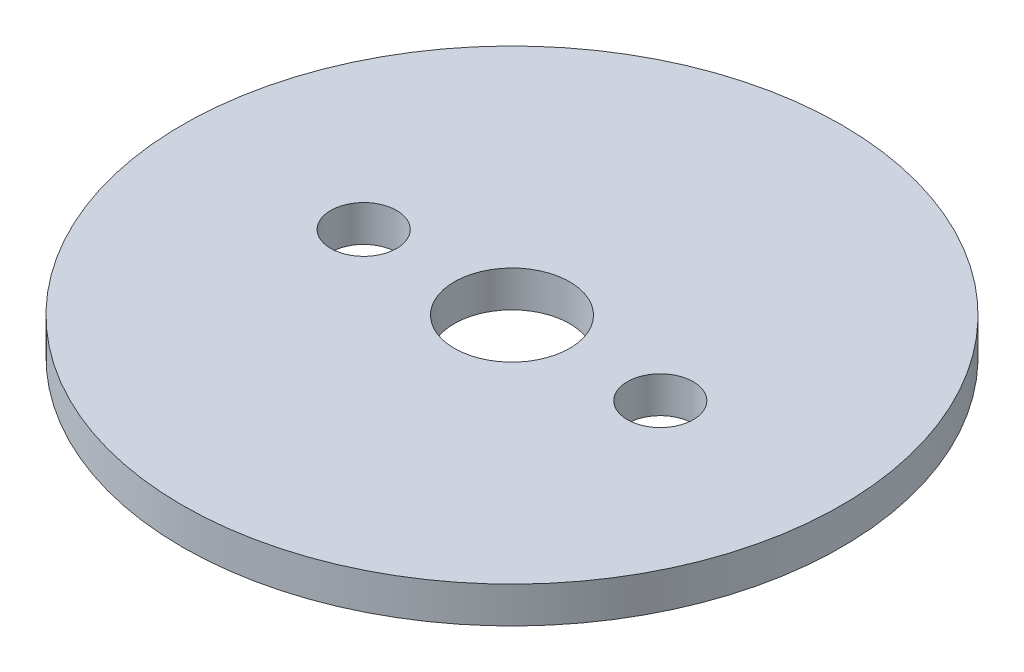
SolidWorks part; units mm, degrees
ref_plane "Спереди" through (0, 0, 0) normal (0, 0, 1) x (1, 0, 0)
ref_plane "Сверху" through (0, 0, 0) normal (0, 1, 0) x (1, 0, 0)
ref_plane "Справа" through (0, 0, 0) normal (1, 0, 0) x (0, 0, -1)
other "Configuration Table"
sketch "Эскиз1" plane through (0, 0, 0) normal (0, 1, 0) x (1, 0, 0)
  circle A0 centre (0, 0) radius 100
  circle A1 centre (0, 0) radius 17.5
  circle A2 centre (-45, 0) radius 10
  circle A3 centre (45, 0) radius 10
  dimension "D1" = 200
  dimension "D2" = 35
  dimension "D3" = 45
  dimension "D4" = 45
extrude "Бобышка-Вытянуть1" add sketch "Эскиз1" against normal blind 11
